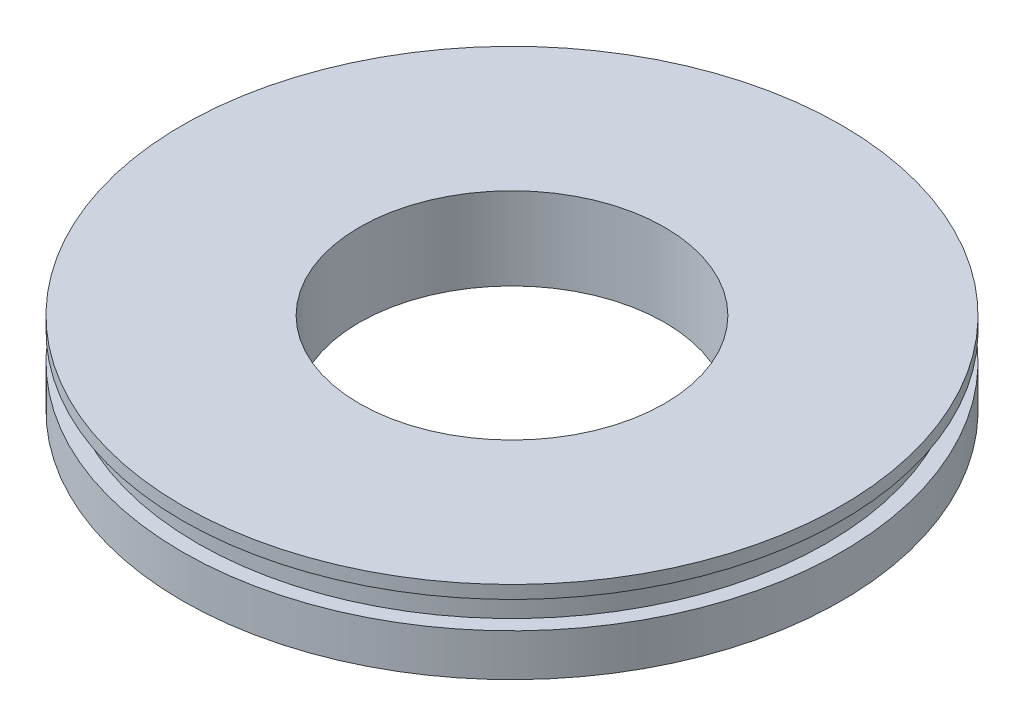
SolidWorks part; units mm, degrees
material "6061-T6 (SS)"
ref_plane "X-Y Datum" through (0, 0, 0) normal (0, 0, 1) x (1, 0, 0)
ref_plane "X-Z Datum" through (0, 0, 0) normal (0, 1, 0) x (1, 0, 0)
ref_plane "Y-Z Datum" through (0, 0, 0) normal (1, 0, 0) x (0, 0, -1)
sketch "Sketch1" plane through (0, 0, 0) normal (1, 0, 0) x (0, 0, -1)
  line L0 (-14.2875, 2.6941) -> (-14.2875, -5.0208)
  line L1 (-14.2875, -5.0208) -> (-30.8407, -5.0208)
  line L3 (-30.8407, -1.0621) -> (-29.4348, -1.0621)
  line L4 (-29.4348, -1.0621) -> (-29.4348, 1.4779)
  line L5 (-29.4348, 1.4779) -> (-30.8407, 1.4779)
  line L6 (-30.8407, 1.4779) -> (-30.8407, 2.6941)
  line L7 (-30.8407, 2.6941) -> (-14.2875, 2.6941)
  line L8 (0, 0) -> (0, -47872.0541) construction
  line L9 (0, 0) -> (-47872.0541, 0) construction
  line L10 (-30.8407, -1.0621) -> (-30.8407, -5.0208)
  line L11 (-14.7421, 2.6941) -> (15.0495, 2.6941) construction
  line L12 (-30.9994, 12.7) -> (-30.9994, -12.7) construction
  line L13 (14.2875, -5.0208) -> (-14.2875, -5.0208) construction
  line L14 (-29.3688, -1.0621) -> (29.3687, -1.0621) construction
  circle A0 centre (-30.3238, 0.2079) radius 0.889 construction
  point P15 (-30.9994, 0)
  point P16 (-29.4348, 0.2079)
  dimension "D3" = 1.778
  dimension "D1" = 28.575
  dimension "D2" = 61.6814
  dimension "D4" = 2.54
  dimension "D5" = 25.4
  dimension "D6" = 61.9989
  dimension "D7" = 1.5646
revolve "Revolve1" add sketch "Sketch1" angle 360 about L8
